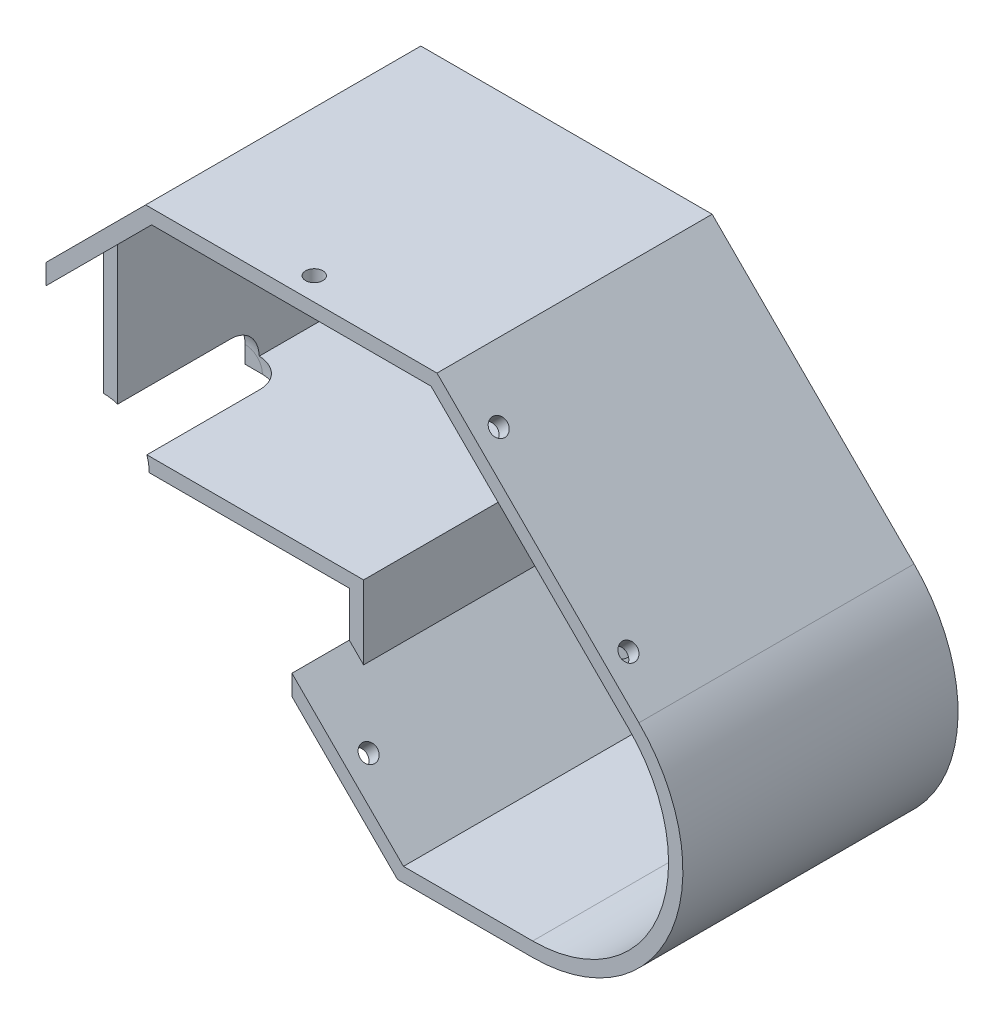
SolidWorks part; units mm, degrees
ref_plane "Plano frontal" through (0, 0, 0) normal (0, 0, 1) x (1, 0, 0)
ref_plane "Plano superior" through (0, 0, 0) normal (0, 1, 0) x (1, 0, 0)
ref_plane "Plano direito" through (0, 0, 0) normal (1, 0, 0) x (0, 0, -1)
sketch "Model" plane through (0, 0, 0) normal (0, 0, 1) x (1, 0, 0)
  line L0 (0, 0) -> (39, 0) construction
  line L1 (-0.7, 2.5) -> (39, 2.5)
  line L2 (39.7, 0) -> (39.7, -6.8548) construction
  line L3 (0, 0) -> (0, 31.4419) construction
  line L4 (50.1111, 46.949) -> (15.5071, 46.949) construction
  line L5 (0, 31.4419) -> (15.5071, 46.949) construction
  line L6 (42.2, -9.3548) -> (52.4452, -19.6) construction
  line L7 (39, -7.1448) -> (51.9502, -20.095) construction
  line L8 (97.9635, 12.6635) -> (63.6779, 46.949) construction
  line L9 (50.1111, 46.949) -> (63.6779, 46.949) construction
  line L10 (52.4452, -19.6) -> (59.4452, -26.6) construction
  line L11 (81.7, -26.6) -> (59.4452, -26.6) construction
  line L12 (-0.7, 0) -> (39, 0)
  line L13 (-0.7, 0) -> (-3.2, 0)
  line L14 (42.2, -10.3448) -> (51.9502, -20.095)
  line L15 (51.9502, -20.095) -> (59.1552, -27.3)
  line L16 (81.7, -27.3) -> (59.1552, -27.3)
  line L17 (98.4584, 13.1584) -> (63.9678, 47.649)
  line L18 (50.1111, 47.649) -> (63.9678, 47.649)
  line L19 (50.1111, 47.649) -> (15.2171, 47.649)
  line L20 (-0.7, 31.7319) -> (15.2171, 47.649)
  line L21 (-0.7, 2.5) -> (-0.7, 31.7319)
  line L22 (0, 0) -> (-0.7, 0) construction
  line L23 (38.8515, -10.5318) -> (50.1824, -21.8627) construction
  line L24 (-3.2, 0) -> (-3.2, 5)
  line L25 (-0.7, -0.7) -> (-0.7, 31.7319) construction
  line L26 (-0.7, -0.7) -> (39, -0.7) construction
  line L27 (39, -0.7) -> (39, -7.1448) construction
  line L28 (39, -0.7) -> (39, -0.7) construction
  line L29 (39, 0) -> (39.7, 0)
  line L30 (39.7, 0) -> (39.7, -11.3803)
  line L31 (39, 2.5) -> (39.7, 2.5)
  line L32 (39.7, 2.5) -> (42.2, 2.5)
  line L33 (39, 0) -> (39.7, 0) construction
  line L34 (42.2, 2.5) -> (42.2, -10.3448)
  line L35 (-3.2, 5) -> (-3.2, 32.7674)
  line L36 (-3.2, 32.7674) -> (14.1816, 50.149)
  line L37 (50.1111, 50.149) -> (14.1816, 50.149)
  line L38 (50.1111, 50.149) -> (65.0034, 50.149)
  line L39 (100.2262, 14.9262) -> (65.0034, 50.149)
  line L40 (81.7, -29.8) -> (58.1197, -29.8)
  line L41 (50.1824, -21.8627) -> (58.1197, -29.8)
  line L42 (39.7, -11.3803) -> (50.1824, -21.8627)
  line L43 (-0.7, 2.5) -> (-5.7, 2.5) construction
  line L44 (-5.7, 0) -> (-5.7, 2.5) construction
  line L45 (-0.7, 0) -> (-5.7, 0) construction
  line L46 (-3.2, 5) -> (-8.2, 5) construction
  line L47 (-8.2, -2.5) -> (-8.2, 5) construction
  line L48 (-0.7, -2.5) -> (39, -2.5) construction
  line L49 (-0.7, -2.5) -> (-8.2, -2.5) construction
  line L51 (40.6192, -8.764) -> (51.9502, -20.095) construction
  line L52 (39.7, -6.8548) -> (52.4452, -19.6) construction
  arc A0 (81.7, -27.3) -> (98.4584, 13.1584) centre (81.7, -3.6) ccw
  arc A1 (81.7, -29.8) -> (100.2262, 14.9262) centre (81.7, -3.6) ccw
  circle A2 centre (59.0726, 19.0274) radius 7.35 construction
  arc A5 (81.7, -26.6) -> (97.9635, 12.6635) centre (81.7, -3.6) ccw construction
  circle A6 centre (81.7, -3.6) radius 7.3 construction
  circle A13 centre (27.384, 23.481) radius 7.35 construction
  dimension "D2" = 2.5
  dimension "D1" = 0.7
extrude "Ressalto-extrusão1" add sketch "Model" along normal blind 48
sketch "Esboço12" plane through (57.5762, 57.5762, 0) normal (0.7071, 0.7071, 0) x (0, 0, -1)
  line L0 (-48, -35.4099) -> (-44, -35.4099) construction
  line L1 (-48, -60.3162) -> (-48, -10.5036) construction
  line L2 (-44, -35.4099) -> (-44, -43.4099) construction
  line L7 (-45.4, -52.0727) -> (-44, -52.0727) construction
  line L9 (-45.4, -20.0727) -> (-44, -20.0727) construction
  circle A0 centre (-44, -20.0727) radius 1.5
  circle A1 centre (-44, -52.0727) radius 1.5
extrude "Corte-extrusão10" cut sketch "Esboço12" against normal blind 10
sketch "Esboço13" plane through (0, 50.149, 0) normal (0, 1, 0) x (1, 0, 0)
  line L0 (39.5925, -48) -> (39.5925, -44) construction
  line L1 (65.0034, -48) -> (14.1816, -48) construction
  circle A0 centre (39.5925, -44) radius 1.5
extrude "Corte-extrusão11" cut sketch "Esboço13" against normal blind 10
sketch "Esboço14" plane through (-3.2, 0, 0) normal (-1, 0, 0) x (0, 0, 1)
  line L0 (48, 16.3837) -> (44, 16.3837) construction
  line L1 (48, 32.7674) -> (48, 0) construction
  line L2 (45.3801, 22.301) -> (45.3801, 25.101) construction
  line L3 (45.3626, 6.3583) -> (45.3626, 9.1235) construction
  line L4 (45.3801, 22.301) -> (45.3801, 25.101) construction
  line L5 (45.3626, 6.3583) -> (45.3626, 9.1235) construction
  line L6 (45.3801, 23.701) -> (44, 23.701) construction
  line L7 (45.3626, 7.7409) -> (44, 7.7409) construction
  circle A0 centre (44, 23.701) radius 1.5
  circle A1 centre (44, 7.7409) radius 1.5
extrude "Corte-extrusão12" cut sketch "Esboço14" against normal blind 10
sketch "Esboço15" plane through (14.1598, 14.1598, 0) normal (-0.7071, -0.7071, 0) x (0, 0, 1)
  line L0 (48, -62.1686) -> (44, -62.1686) construction
  line L1 (48, -62.1686) -> (0, -62.1686) construction
  line L2 (0, -36.4548) -> (0, -50.9436) construction
  line L3 (0, -50.9436) -> (0, -60.8431) construction
  line L4 (0, -36.4548) -> (0, -50.9436) construction
  line L5 (0, -50.9436) -> (0, -60.8431) construction
  line L6 (0, -60.8431) -> (0, -36.4548) construction
  line L7 (0, -36.4548) -> (0, -48.6489) construction
  line L8 (0, -48.6489) -> (48, -48.6489) construction
  line L9 (48, -36.1192) -> (48, -62.1686) construction
  line L11 (45.4, -48.2812) -> (45.4, -45.4812) construction
  line L12 (45.4, -48.2812) -> (45.4, -45.4812) construction
  line L13 (45.4, -46.8812) -> (44, -46.8812) construction
  circle A0 centre (44, -46.8812) radius 1.5
extrude "Corte-extrusão13" cut sketch "Esboço15" against normal blind 10
sketch "Esboço16" plane through (0, 0, 48) normal (0, 0, 1) x (1, 0, 0)
  line L0 (39.7, 0) -> (39.7, -7.8448)
  line L3 (42.2, -10.3448) -> (39.7, -7.8448)
  line L4 (42.2, -10.3448) -> (42.2, 2.5)
  line L5 (42.2, 2.5) -> (-0.7, 2.5)
  line L6 (39.7, 0) -> (39.7, -7.8448) construction
  line L12 (-0.7, 0) -> (39.7, 0)
  line L13 (-0.7, 2.5) -> (-0.7, 0)
extrude "Corte-extrusão14" cut sketch "Esboço16" against normal blind 10
sketch "Esboço17" plane through (0, 0, 0) normal (0, 0, -1) x (-1, 0, 0)
  line L0 (-93.3365, 21.8159) -> (-95.4578, 19.6946) construction
  line L1 (-93.3365, 21.8159) -> (-95.4578, 19.6946) construction
  line L2 (-70.709, 44.4433) -> (-72.8304, 42.322) construction
  line L3 (-70.709, 44.4433) -> (-72.8304, 42.322) construction
  line L4 (-38.0925, 50.149) -> (-41.0925, 50.149) construction
  line L5 (-38.0925, 50.149) -> (-41.0925, 50.149) construction
  line L6 (3.2, 22.201) -> (3.2, 25.201) construction
  line L7 (3.2, 22.201) -> (3.2, 25.201) construction
  line L8 (3.2, 6.2409) -> (3.2, 9.2409) construction
  line L9 (3.2, 6.2409) -> (3.2, 9.2409) construction
  line L10 (-48.3705, -20.0508) -> (-46.2492, -17.9295) construction
  line L11 (-48.3705, -20.0508) -> (-46.2492, -17.9295) construction
  line L12 (-94.3971, 20.7553) -> (-91.5687, 17.9268) construction
  line L14 (-39.5925, 50.149) -> (-39.5925, 46.149) construction
  line L18 (-69.8727, 39.6229) -> (-67.0727, 39.6229)
  line L19 (-92.9687, 19.3268) -> (-90.1687, 19.3268)
  line L20 (-92.9687, 19.3268) -> (-92.9687, 16.5268)
  line L21 (-92.9687, 16.5268) -> (-90.1687, 16.5268)
  line L22 (-90.1687, 19.3268) -> (-90.1687, 16.5268)
  line L23 (-92.9687, 19.3268) -> (-90.1687, 16.5268) construction
  line L24 (-92.9687, 16.5268) -> (-90.1687, 19.3268) construction
  line L25 (-69.8727, 39.6229) -> (-67.0727, 42.4229) construction
  line L26 (-69.8727, 42.4229) -> (-67.0727, 39.6229) construction
  line L27 (-69.8727, 42.4229) -> (-69.8727, 39.6229)
  line L28 (-69.8727, 42.4229) -> (-67.0727, 42.4229)
  line L29 (-67.0727, 42.4229) -> (-67.0727, 39.6229)
  line L30 (-38.1925, 47.549) -> (-38.1925, 44.749)
  line L31 (-40.9925, 44.749) -> (-38.1925, 47.549) construction
  line L32 (-40.9925, 47.549) -> (-40.9925, 44.749)
  line L33 (-40.9925, 47.549) -> (-38.1925, 44.749) construction
  line L34 (-40.9925, 44.749) -> (-38.1925, 44.749)
  line L35 (-40.9925, 47.549) -> (-38.1925, 47.549)
  line L36 (-2.2, 25.7837) -> (0.6, 22.9837) construction
  line L37 (-2.2, 22.9837) -> (0.6, 22.9837)
  line L38 (0.6, 25.7837) -> (0.6, 22.9837)
  line L39 (-2.2, 25.7837) -> (0.6, 25.7837)
  line L40 (-2.2, 22.9837) -> (0.6, 25.7837) construction
  line L41 (-2.2, 25.7837) -> (-2.2, 22.9837)
  line L42 (0.6, 9.7837) -> (0.6, 6.9837)
  line L43 (-2.2, 9.7837) -> (0.6, 9.7837)
  line L44 (-2.2, 6.9837) -> (0.6, 6.9837)
  line L45 (-2.2, 9.7837) -> (0.6, 6.9837) construction
  line L46 (-2.2, 9.7837) -> (-2.2, 6.9837)
  line L47 (-2.2, 6.9837) -> (0.6, 9.7837) construction
  line L48 (-52.7883, -18.8117) -> (-49.9883, -18.8117)
  line L49 (-52.7883, -16.0117) -> (-49.9883, -18.8117) construction
  line L50 (-52.7883, -18.8117) -> (-49.9883, -16.0117) construction
  line L51 (-52.7883, -16.0117) -> (-49.9883, -16.0117)
  line L52 (-49.9883, -16.0117) -> (-49.9883, -18.8117)
  line L53 (-52.7883, -16.0117) -> (-52.7883, -18.8117)
  circle A0 centre (-91.5687, 17.9268) radius 4
  circle A1 centre (-68.4727, 41.0229) radius 4
  circle A2 centre (-39.5925, 46.149) radius 4
  circle A3 centre (-0.8, 24.3837) radius 4
  circle A4 centre (-0.8, 8.3837) radius 4
  circle A5 centre (-51.3883, -17.4117) radius 4
extrude "Ressalto-extrusão2" add sketch "Esboço17" against normal blind 4
sketch "Esboço18" plane through (0, 0, 48) normal (0, 0, 1) x (1, 0, 0)
  line L0 (-0.7, 31.7319) -> (-32.4319, 0)
  line L1 (15.2171, 47.649) -> (-0.7, 31.7319) construction
  line L2 (-0.7, 31.7319) -> (-0.7, 0)
  line L3 (-0.7, 0) -> (-32.4319, 0)
extrude "Corte-extrusão15" cut sketch "Esboço18" against normal up to surface (10 mm away) up to face at (27.0667, -2.1983, 38)
sketch "Esboço19" plane through (-3.2, 0, 0) normal (-1, 0, 0) x (0, 0, 1)
  line L0 (48, -11.3803) -> (0, -11.3803) construction
  line L1 (48, -11.3803) -> (0, -11.3803) construction
  line L2 (24, -11.3803) -> (24, 0) construction
  line L3 (38, 0) -> (0, 0) construction
  line L4 (38.2569, 0) -> (13.2569, 0)
  line L5 (13.2569, 0) -> (13.2569, 3)
  line L7 (13.2569, 3) -> (23.2569, 3) construction
  line L8 (18.2569, 8) -> (38.2569, 8)
  line L9 (38.2569, 8) -> (38.2569, 0)
  arc A0 (18.2569, 8) -> (13.2569, 3) centre (18.2569, 3) ccw
revolve "Corte-Revolução1" cut sketch "Esboço19" angle 360 about L4
